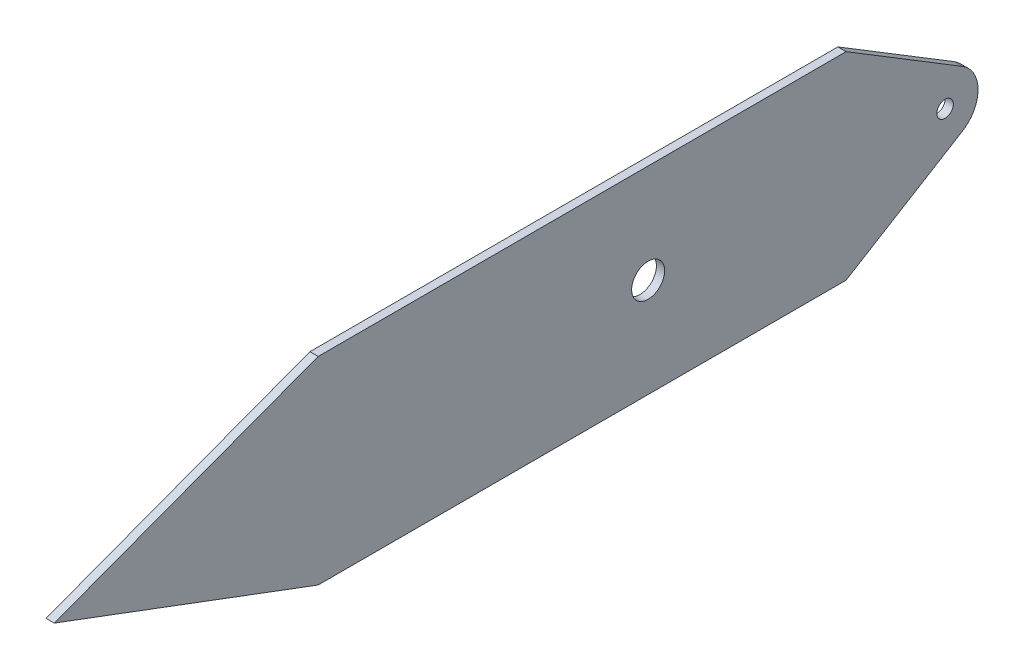
SolidWorks part; units mm, degrees
ref_plane "Front Plane" through (0, 0, 0) normal (1, 0, 0) x (0, 1, 0)
ref_plane "Top Plane" through (0, 0, 0) normal (0, 0, 1) x (0, 1, 0)
ref_plane "Right Plane" through (0, 0, 0) normal (0, 1, 0) x (-1, 0, 0)
sketch "Sketch1" plane through (0, 0, 0) normal (1, 0, 0) x (0, 1, 0)
  line L0 (-38.1, 127) -> (0, 228.6)
  line L1 (0, 228.6) -> (38.1, 127)
  line L2 (38.1, 127) -> (38.1, -76.2)
  line L4 (-38.1, -76.2) -> (-38.1, 127)
  line L5 (-10.8439, -120.9106) -> (-38.1, -76.2)
  line L6 (-25.4, -148.1667) -> (25.4, -148.1667)
  line L7 (-25.4, -148.1667) -> (-12.7, -97.3667)
  line L8 (-12.7, -97.3667) -> (12.7, -97.3667)
  line L9 (25.4, -148.1667) -> (12.7, -97.3667)
  line L10 (-25.4, -148.1667) -> (12.7, -97.3667) construction
  line L11 (-12.7, -97.3667) -> (25.4, -148.1667) construction
  line L12 (10.8439, -120.9106) -> (38.1, -76.2)
  line L13 (-38.1, -76.2) -> (38.1, -76.2) construction
  circle A0 centre (0, 0) radius 6.35
  arc A1 (-10.8439, -120.9106) -> (10.8439, -120.9106) centre (0, -114.3) ccw
  circle A2 centre (0, -114.3) radius 3.175
  circle A3 centre (0, -114.3) radius 3.175
  point P9 (0, -76.2)
  point P10 (35.4103, 104.6363)
  point P12 (0, -114.3)
  point P19 (-42.4651, -196.9532)
  point P20 (-0.6248, -108.5613)
  point P21 (0, -97.3667)
  point P22 (0, -148.1667)
  point P23 (38.1, 138.8485)
  point P24 (0, 234.6177)
  point P25 (-38.1, -68.6026)
  point P26 (-10.8439, -149.43)
  point P28 (0, 0)
  point P29 (12.7, -128.6274)
  point P30 (38.1, 124.0119)
  point P31 (38.1, 25.4)
  dimension "D4" = 6.35
  dimension "D9" = 12.7
  dimension "D10" = 12.7
  dimension "D1" = 25.4
  dimension "D2" = 50.8
  dimension "D3" = 50.8
  dimension "D5" = 76.2
  dimension "D6" = 50.8
  dimension "D7" = 101.6
  dimension "D8" = 203.2
  dimension "D11" = 25.4
extrude "Boss-Extrude1" add sketch "Sketch1" along normal blind 3.175 contours L9 L12 L2 L1 L0 L4 L5 L7 L8 A0 | L5 A1 L12 L9 L8 L7 A2
